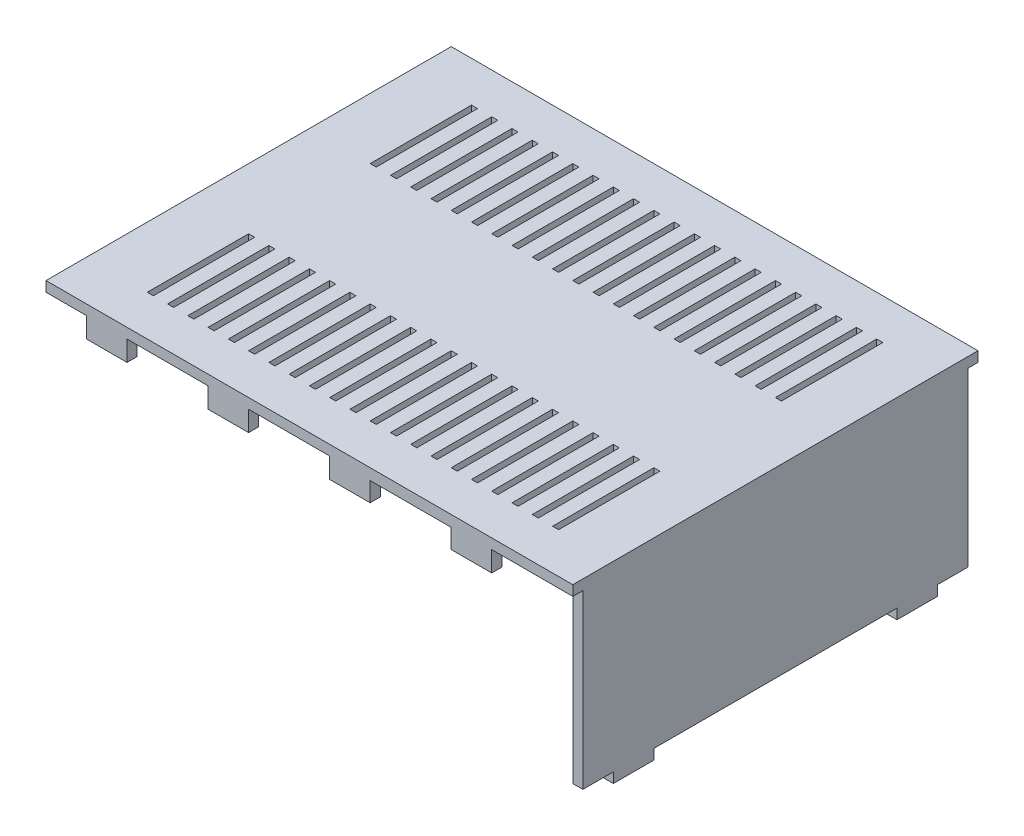
SolidWorks part; units mm, degrees
ref_plane "Front Plane" through (0, 0, 0) normal (0, 0, 1) x (1, 0, 0)
ref_plane "Top Plane" through (0, 0, 0) normal (0, 1, 0) x (1, 0, 0)
ref_plane "Right Plane" through (0, 0, 0) normal (1, 0, 0) x (0, 0, -1)
sketch "Sketch2" plane through (0, 0, 0) normal (0, 1, 0) x (1, 0, 0)
  line L1 (65, -50) -> (-65, -50)
  line L2 (65, -50) -> (65, 50)
  line L3 (65, 50) -> (-65, 50)
  line L4 (-65, -50) -> (-65, 50)
  line L5 (65, -50) -> (-65, 50) construction
  line L6 (65, 50) -> (-65, -50) construction
  point P0 (0, 0)
  dimension "D1" = 100
  dimension "D2" = 130
extrude "Boss-Extrude3" add sketch "Sketch2" along normal blind 7.5
sketch "Sketch5" plane through (0, 0, 0) normal (0, -1, 0) x (1, 0, 0)
  line L0 (-65, -50) -> (-65, 50) construction
  line L1 (62.5, -47.5) -> (-62.5, -47.5)
  line L2 (62.5, -47.5) -> (62.5, 47.5)
  line L3 (62.5, 47.5) -> (-62.5, 47.5)
  line L4 (-62.5, -47.5) -> (-62.5, 47.5)
  line L5 (62.5, -47.5) -> (-62.5, 47.5) construction
  line L6 (62.5, 47.5) -> (-62.5, -47.5) construction
  line L7 (-65, 50) -> (65, 50) construction
  point P0 (0, 0)
  dimension "D1" = 2.5
  dimension "D2" = 2.5
extrude "Cut-Extrude1" cut sketch "Sketch5" against normal blind 2.5
sketch "Sketch12" plane through (0, 0, -50) normal (0, 0, -1) x (-1, 0, 0)
  line L1 (65, 0) -> (55, 0)
  line L2 (65, 0) -> (65, 5)
  line L3 (65, 5) -> (55, 5)
  line L4 (55, 0) -> (55, 5)
  dimension "D1" = 10
  dimension "D2" = 5
extrude "Cut-Extrude7" cut sketch "Sketch12" against normal blind 2.5
sketch "Sketch13" plane through (0, 2.5, 0) normal (0, -1, 0) x (1, 0, 0)
  line L1 (62.5, -47.5) -> (-62.5, -47.5)
  line L2 (62.5, -47.5) -> (62.5, 47.5)
  line L3 (62.5, 47.5) -> (-62.5, 47.5)
  line L4 (-62.5, -47.5) -> (-62.5, 47.5)
  line L5 (62.5, -47.5) -> (-62.5, 47.5) construction
  line L6 (62.5, 47.5) -> (-62.5, -47.5) construction
  point P0 (0, 0)
extrude "Cut-Extrude8" cut sketch "Sketch13" against normal blind 2.5
sketch "Sketch14" plane through (0, 0, 50) normal (0, 0, 1) x (1, 0, 0)
  line L1 (-65, 0) -> (-55, 0)
  line L2 (-65, 0) -> (-65, 5)
  line L3 (-65, 5) -> (-55, 5)
  line L4 (-55, 0) -> (-55, 5)
  dimension "D1" = 10
  dimension "D2" = 5
extrude "Cut-Extrude9" cut sketch "Sketch14" against normal blind 2.5 contours L2 L1 L4 L3
sketch "Sketch15" plane through (0, 0, 50) normal (0, 0, 1) x (1, 0, 0)
  line L0 (-55, 0) -> (65, 0) construction
  line L1 (-45, 0) -> (-25, 0)
  line L2 (-45, 0) -> (-45, 5)
  line L3 (-45, 5) -> (-25, 5)
  line L4 (-25, 0) -> (-25, 5)
  line L5 (-55, 0) -> (-55, 5) construction
  dimension "D1" = 20
  dimension "D2" = 5
  dimension "D3" = 10
extrude "Cut-Extrude10" cut sketch "Sketch15" against normal blind 2.5
sketch "Sketch16" plane through (0, 0, 50) normal (0, 0, 1) x (1, 0, 0)
  line L0 (-25, 0) -> (65, 0) construction
  line L1 (-15, 0) -> (5, 0)
  line L2 (-15, 0) -> (-15, 5)
  line L3 (-15, 5) -> (5, 5)
  line L4 (5, 0) -> (5, 5)
  line L5 (-25, 0) -> (-25, 5) construction
  point P8 (-15, 2.5)
  dimension "D1" = 20
  dimension "D2" = 5
  dimension "D3" = 10
extrude "Cut-Extrude11" cut sketch "Sketch16" against normal blind 2.5
sketch "Sketch17" plane through (0, 0, 50) normal (0, 0, 1) x (1, 0, 0)
  line L0 (5, 0) -> (5, 5) construction
  line L1 (15, -0.2527) -> (35, -0.2527)
  line L2 (15, -0.2527) -> (15, 4.7473)
  line L3 (15, 4.7473) -> (35, 4.7473)
  line L4 (35, -0.2527) -> (35, 4.7473)
  dimension "D1" = 20
  dimension "D2" = 5
  dimension "D3" = 10
extrude "Cut-Extrude12" cut sketch "Sketch17" against normal blind 2.5
sketch "Sketch27" plane through (0, 0, -50) normal (0, 0, -1) x (-1, 0, 0)
  line L0 (-65, 0) -> (55, 0) construction
  line L1 (45, 0) -> (25, 0)
  line L2 (45, 0) -> (45, 5)
  line L3 (45, 5) -> (25, 5)
  line L4 (25, 0) -> (25, 5)
  line L5 (55, 5) -> (55, 0) construction
  dimension "D1" = 20
  dimension "D2" = 5
  dimension "D3" = 10
extrude "Cut-Extrude22" cut sketch "Sketch27" against normal blind 2.5
sketch "Sketch29" plane through (0, 0, -50) normal (0, 0, -1) x (-1, 0, 0)
  line L0 (-65, 0) -> (25, 0) construction
  line L1 (15, 0) -> (-5, 0)
  line L2 (15, 0) -> (15, 5)
  line L3 (15, 5) -> (-5, 5)
  line L4 (-5, 0) -> (-5, 5)
  line L5 (25, 5) -> (25, 0) construction
  dimension "D1" = 20
  dimension "D2" = 10
  dimension "D3" = 5
extrude "Cut-Extrude23" cut sketch "Sketch29" against normal blind 2.5
sketch "Sketch30" plane through (0, 0, -50) normal (0, 0, -1) x (-1, 0, 0)
  line L0 (-65, 0) -> (-5, 0) construction
  line L1 (-15, 0) -> (-35, 0)
  line L2 (-15, 0) -> (-15, 5)
  line L3 (-15, 5) -> (-35, 5)
  line L4 (-35, 0) -> (-35, 5)
  line L5 (-5, 5) -> (-5, 0) construction
  dimension "D1" = 20
  dimension "D2" = 5
  dimension "D3" = 10
extrude "Cut-Extrude24" cut sketch "Sketch30" against normal blind 2.5
sketch "Sketch25" plane through (0, 7.5, 0) normal (0, 1, 0) x (1, 0, 0)
  line L0 (65, 50) -> (-65, 50) construction
  line L1 (-50, 40) -> (-48.5, 40)
  line L2 (-50, 40) -> (-50, 15)
  line L3 (-50, 15) -> (-48.5, 15)
  line L4 (-48.5, 40) -> (-48.5, 15)
  line L5 (-65, 50) -> (-65, -50) construction
  dimension "D1" = 1.5
  dimension "D2" = 25
  dimension "D3" = 10
  dimension "D4" = 15
extrude "Cut-Extrude19" cut sketch "Sketch25" against normal blind 2.5
pattern_linear "LPattern1" count 21 spacing 5 along (1, 0, 0) count 2 spacing 55 along (0, 0, 1) of "Cut-Extrude19"
sketch "Sketch26" plane through (0, 0, 50) normal (0, 0, 1) x (1, 0, 0)
  line L0 (35, 0) -> (65, 0) construction
  line L1 (45, 0) -> (65, 0)
  line L2 (45, 0) -> (45, 5)
  line L3 (45, 5) -> (65, 5)
  line L4 (65, 0) -> (65, 5)
  line L5 (65, 7.5) -> (65, 0) construction
  dimension "D1" = 20
  dimension "D2" = 5
extrude "Cut-Extrude20" cut sketch "Sketch26" against normal blind 2.5
sketch "Sketch31" plane through (0, 0, -50) normal (0, 0, -1) x (-1, 0, 0)
  line L0 (-65, 0) -> (-35, 0) construction
  line L1 (-45, 0) -> (-65, 0)
  line L2 (-45, 0) -> (-45, 5)
  line L3 (-45, 5) -> (-65, 5)
  line L4 (-65, 0) -> (-65, 5)
  line L5 (-65, 7.5) -> (-65, 0) construction
  dimension "D1" = 20
  dimension "D2" = 5
extrude "Cut-Extrude25" cut sketch "Sketch31" against normal blind 2.5
sketch "Sketch32" plane through (0, 0, 0) normal (0, -1, 0) x (1, 0, 0)
  line L1 (62.5, 47.5) -> (65, 47.5)
  line L2 (62.5, 47.5) -> (62.5, -47.5)
  line L3 (62.5, -47.5) -> (65, -47.5)
  line L4 (65, 47.5) -> (65, -47.5)
extrude "Boss-Extrude4" add sketch "Sketch32" along normal blind 40
sketch "Sketch33" plane through (-65, 0, 0) normal (-1, 0, 0) x (0, 0, 1)
  line L1 (-50, 0) -> (-40, 0)
  line L2 (-50, 0) -> (-50, 5)
  line L3 (-50, 5) -> (-40, 5)
  line L4 (-40, 0) -> (-40, 5)
  dimension "D1" = 10
  dimension "D2" = 5
extrude "Cut-Extrude26" cut sketch "Sketch33" against normal blind 2.5
sketch "Sketch34" plane through (-65, 0, 0) normal (-1, 0, 0) x (0, 0, 1)
  line L0 (-40, 0) -> (47.5, 0) construction
  line L1 (-30, 0) -> (-5, 0)
  line L2 (-30, 0) -> (-30, 5)
  line L3 (-30, 5) -> (-5, 5)
  line L4 (-5, 0) -> (-5, 5)
  line L5 (-40, 0) -> (-40, 5) construction
  dimension "D1" = 25
  dimension "D2" = 5
  dimension "D3" = 10
extrude "Cut-Extrude29" cut sketch "Sketch34" against normal blind 2.5
sketch "Sketch37" plane through (-65, 0, 0) normal (-1, 0, 0) x (0, 0, 1)
  line L0 (-5, 0) -> (47.5, 0) construction
  line L1 (5, 0) -> (30, 0)
  line L2 (5, 0) -> (5, 5)
  line L3 (5, 5) -> (30, 5)
  line L4 (30, 0) -> (30, 5)
  line L5 (-5, 0) -> (-5, 5) construction
  point P8 (5, 2.5)
  dimension "D1" = 25
  dimension "D2" = 5
  dimension "D3" = 10
extrude "Cut-Extrude30" cut sketch "Sketch37" against normal blind 2.5
sketch "Sketch38" plane through (-65, 0, 0) normal (-1, 0, 0) x (0, 0, 1)
  line L0 (30, 0) -> (47.5, 0) construction
  line L1 (40, 0) -> (50, 0)
  line L2 (40, 0) -> (40, 5)
  line L3 (40, 5) -> (50, 5)
  line L4 (50, 0) -> (50, 5)
  dimension "D1" = 10
extrude "Cut-Extrude31" cut sketch "Sketch38" against normal blind 2.5
sketch "Sketch39" plane through (0, -40, 0) normal (0, -1, 0) x (1, 0, 0)
  line L0 (62.5, -47.5) -> (62.5, 47.5) construction
  line L1 (65, -50) -> (62.5, -50)
  line L2 (65, -50) -> (65, -40)
  line L3 (65, -40) -> (62.5, -40)
  line L4 (62.5, -50) -> (62.5, -40)
  dimension "D1" = 10
extrude "Cut-Extrude32" cut sketch "Sketch39" against normal blind 2.5
sketch "Sketch40" plane through (0, -40, 0) normal (0, -1, 0) x (1, 0, 0)
  line L0 (62.5, 47.5) -> (62.5, -40) construction
  line L1 (65, 50) -> (62.5, 50)
  line L2 (65, 50) -> (65, 40)
  line L3 (65, 40) -> (62.5, 40)
  line L4 (62.5, 50) -> (62.5, 40)
  dimension "D1" = 10
extrude "Cut-Extrude33" cut sketch "Sketch40" against normal blind 2.5
sketch "Sketch41" plane through (0, -40, 0) normal (0, -1, 0) x (1, 0, 0)
  line L0 (65, -40) -> (65, 40) construction
  line L1 (65, -30) -> (62.5, -30)
  line L2 (65, -30) -> (65, 30)
  line L3 (65, 30) -> (62.5, 30)
  line L4 (62.5, -30) -> (62.5, 30)
  line L5 (62.5, 40) -> (62.5, -40) construction
  line L6 (65, -40) -> (62.5, -40) construction
  dimension "D1" = 60
  dimension "D2" = 10
extrude "Cut-Extrude35" cut sketch "Sketch41" against normal blind 2.5
